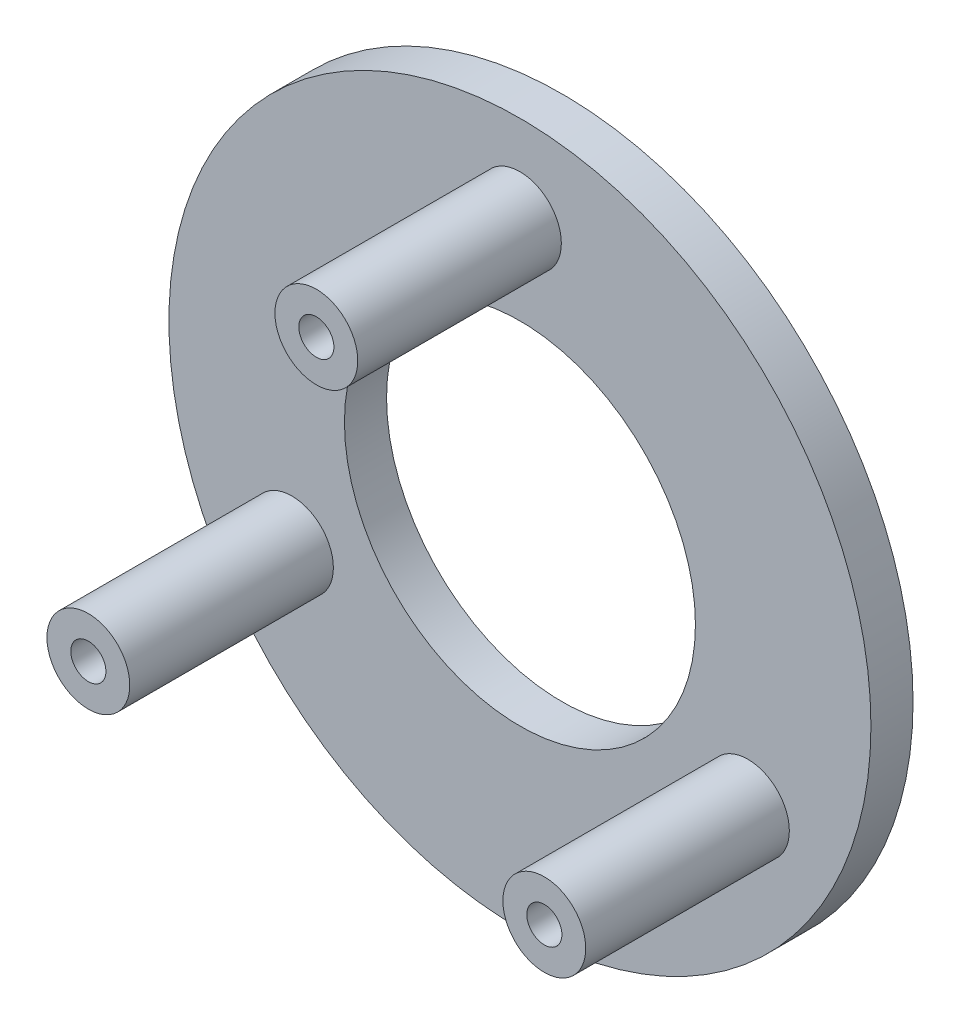
SolidWorks part; units mm, degrees
ref_plane "Front Plane" through (0, 0, 0) normal (0, 0, 1) x (1, 0, 0)
ref_plane "Top Plane" through (0, 0, 0) normal (0, 1, 0) x (1, 0, 0)
ref_plane "Right Plane" through (0, 0, 0) normal (1, 0, 0) x (0, 0, -1)
sketch "Sketch1" plane through (0, 0, 0) normal (0, 0, 1) x (1, 0, 0)
  line L0 (0, 0) -> (0, 18.75) construction
  line L1 (0, 0) -> (0, 18.75) construction
  circle A0 centre (0, 0) radius 12.5
  circle A1 centre (0, 0) radius 25
  circle A2 centre (0, 18.75) radius 2.95
  circle A3 centre (16.238, -9.375) radius 2.95
  circle A4 centre (-16.238, -9.375) radius 2.95
  dimension "D2" = 25
  dimension "D3" = 50
  dimension "D4" = 5.9
  dimension "D6" = 18.75
  dimension "D5" = 3
extrude "Boss-Extrude1" add sketch "Sketch1" along normal blind 3
sketch "Sketch4" plane through (0, 0, 0) normal (0, 0, -1) x (-1, 0, 0)
  circle A0 centre (16.238, -9.375) radius 2.95 construction
  circle A1 centre (0, 18.75) radius 2.95 construction
  circle A2 centre (-16.238, -9.375) radius 2.95 construction
  circle A3 centre (16.238, -9.375) radius 2.95
  circle A4 centre (0, 18.75) radius 2.95
  circle A5 centre (-16.238, -9.375) radius 2.95
extrude "Boss-Extrude3" add sketch "Sketch4" against normal blind 17.5
sketch "Sketch5" plane through (0, 0, 17.5) normal (0, 0, 1) x (1, 0, 0)
  circle A0 centre (16.238, -9.375) radius 1.25
  circle A1 centre (-16.238, -9.375) radius 1.25
  circle A2 centre (0, 18.75) radius 1.25
  dimension "D1" = 2.5
extrude "Cut-Extrude2" cut sketch "Sketch5" against normal blind 8
